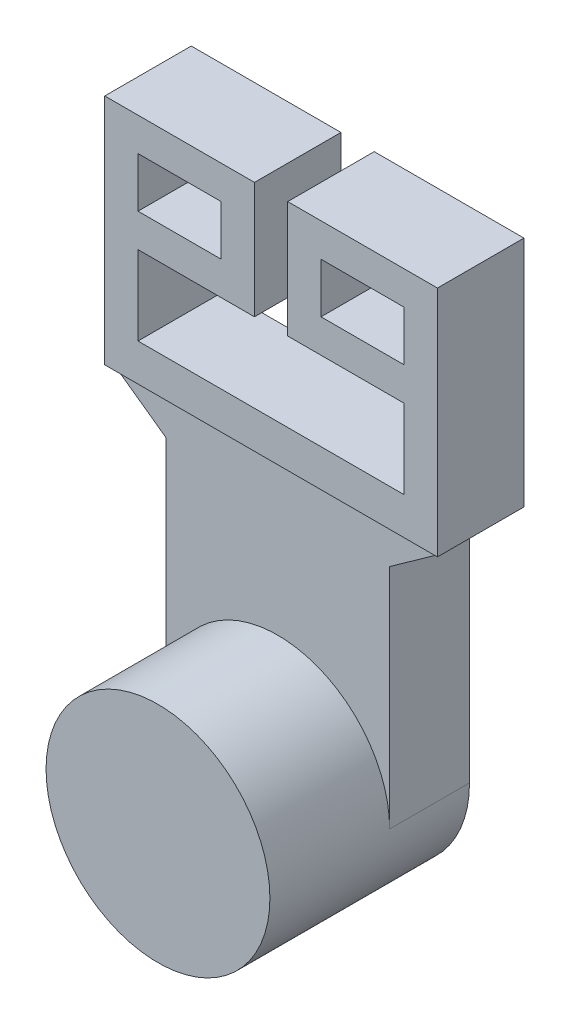
SolidWorks part; units mm, degrees
ref_plane "Front Plane" through (0, 0, 0) normal (0, 0, 1) x (1, 0, 0)
ref_plane "Top Plane" through (0, 0, 0) normal (0, 1, 0) x (1, 0, 0)
ref_plane "Right Plane" through (0, 0, 0) normal (1, 0, 0) x (0, 0, -1)
sketch "Sketch1" plane through (0, 0, 0) normal (0, 0, 1) x (1, 0, 0)
  circle A0 centre (0, 0) radius 10.6807
  dimension "D1" = 21.3614
extrude "Boss-Extrude1" add sketch "Sketch1" along normal blind 19.05
sketch "Sketch2" plane through (0, 0, 0) normal (0, 0, -1) x (-1, 0, 0)
  line L0 (10.6807, 0) -> (-10.6807, 0)
  line L1 (-10.6807, 0) -> (-10.6807, 25.4)
  line L2 (10.6807, 0) -> (10.6807, 25.4)
  line L3 (-10.6807, 25.4) -> (10.6807, 25.4)
  circle A0 centre (0, 0) radius 10.6807 construction
extrude "Boss-Extrude2" add sketch "Sketch2" against normal blind 7.62
sketch "Sketch3" plane through (0, 25.4, 0) normal (0, 1, 0) x (1, 0, 0)
  line L0 (0, 0) -> (12.7, 0)
  line L1 (0, 0) -> (-12.7, 0)
  line L2 (12.7, 0) -> (12.7, -15.875)
  line L3 (-12.7, 0) -> (-12.7, -15.875)
  line L4 (-12.7, -15.875) -> (12.7, -15.875)
extrude "Boss-Extrude3" add sketch "Sketch3" along normal blind 3.556
sketch "Sketch4" plane through (12.7, 0, 0) normal (1, 0, 0) x (0, 0, -1)
  line L5 (0, 25.4) -> (-15.875, 25.4)
  line L6 (0, 25.4) -> (0, 47.625)
  line L7 (0, 47.625) -> (-15.875, 47.625)
  line L8 (-15.875, 25.4) -> (-15.875, 47.625)
extrude "Boss-Extrude4" add sketch "Sketch4" along normal blind 3.175
sketch "Sketch5" plane through (-12.7, 0, 0) normal (-1, 0, 0) x (0, 0, 1)
  line L1 (15.875, 25.4) -> (0, 25.4)
  line L2 (15.875, 25.4) -> (15.875, 47.625)
  line L3 (15.875, 47.625) -> (0, 47.625)
  line L4 (0, 25.4) -> (0, 47.625)
extrude "Boss-Extrude5" add sketch "Sketch5" along normal blind 3.175
sketch "Sketch7" plane through (-12.7, 0, 0) normal (1, 0, 0) x (0, 0, -1)
  line L0 (-15.875, 47.625) -> (-15.875, 36.5125)
  line L1 (-15.875, 47.625) -> (-15.875, 25.4) construction
  line L2 (-15.875, 36.5125) -> (0, 36.5125)
  line L3 (0, 25.4) -> (0, 47.625) construction
  line L4 (0, 36.5125) -> (0, 47.625)
  line L5 (0, 47.625) -> (-15.875, 47.625)
extrude "Boss-Extrude6" add sketch "Sketch7" along normal blind 11.1125
sketch "Sketch8" plane through (12.7, 0, 0) normal (-1, 0, 0) x (0, 0, 1)
  line L1 (15.875, 36.5125) -> (0, 36.5125)
  line L2 (15.875, 36.5125) -> (15.875, 47.625)
  line L3 (15.875, 47.625) -> (0, 47.625)
  line L4 (0, 36.5125) -> (0, 47.625)
extrude "Boss-Extrude7" add sketch "Sketch8" along normal blind 11.1125
sketch "Sketch9" plane through (0, 0, 15.875) normal (0, 0, 1) x (1, 0, 0)
  line L1 (-15.875, 25.4) -> (15.875, 25.4)
  line L2 (-15.875, 25.4) -> (-15.875, 47.625)
  line L3 (-15.875, 47.625) -> (15.875, 47.625)
  line L4 (15.875, 25.4) -> (15.875, 47.625)
extrude "Cut-Extrude1" cut sketch "Sketch9" against normal blind 7.62
sketch "Sketch10" plane through (0, 0, 0) normal (0, 0, -1) x (-1, 0, 0)
  line L0 (-10.6807, 25.4) -> (-15.875, 25.4)
  line L1 (-15.875, 25.4) -> (-10.6807, 21.6843)
  line L2 (-10.6807, 25.4) -> (-10.6807, 0) construction
  line L3 (-10.6807, 21.6843) -> (-10.6807, 25.4)
  line L4 (0, 27.5295) -> (0, 19.0026) construction
  line L5 (15.875, 25.4) -> (10.6807, 21.6843)
  line L6 (10.6807, 25.4) -> (15.875, 25.4)
  line L7 (10.6807, 21.6843) -> (10.6807, 25.4)
extrude "Boss-Extrude8" add sketch "Sketch10" against normal blind 7.62
sketch "Sketch11" plane through (0, 0, 8.255) normal (0, 0, 1) x (1, 0, 0)
  line L6 (12.7, 44.45) -> (4.7625, 44.45)
  line L7 (0, 42.0687) -> (0, 36.988) construction
  line L8 (-12.7, 39.6875) -> (-4.7625, 39.6875)
  line L9 (-12.7, 39.6875) -> (-12.7, 44.45)
  line L10 (-12.7, 44.45) -> (-4.7625, 44.45)
  line L11 (-4.7625, 39.6875) -> (-4.7625, 44.45)
  line L12 (4.7625, 39.6875) -> (4.7625, 44.45)
  line L13 (12.7, 39.6875) -> (4.7625, 39.6875)
  line L14 (12.7, 39.6875) -> (12.7, 44.45)
extrude "Cut-Extrude2" cut sketch "Sketch11" against normal up to next
sketch "Sketch12" plane through (0, 0, 7.62) normal (0, 0, 1) x (1, 0, 0)
  line L8 (7.5057, 13.8557) -> (-7.5057, 13.8557)
  line L9 (7.5057, 13.8557) -> (7.5057, 22.225)
  line L10 (7.5057, 22.225) -> (-7.5057, 22.225)
  line L11 (-7.5057, 13.8557) -> (-7.5057, 22.225)
